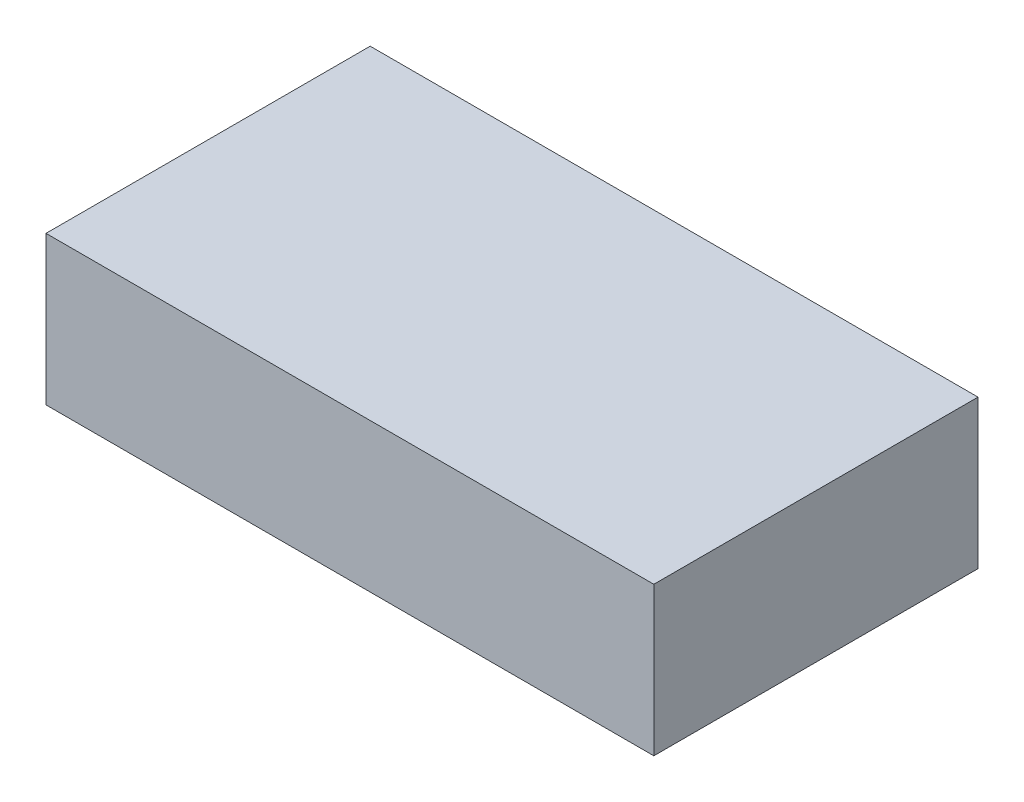
SolidWorks part; units mm, degrees
ref_plane "Front Plane" through (0, 0, 0) normal (0, 0, 1) x (1, 0, 0)
ref_plane "Top Plane" through (0, 0, 0) normal (0, 1, 0) x (1, 0, 0)
ref_plane "Right Plane" through (0, 0, 0) normal (1, 0, 0) x (0, 0, -1)
sketch "Sketch1" plane through (0, 0, 0) normal (0, 1, 0) x (1, 0, 0)
  line L1 (0, 0) -> (-45, 0)
  line L2 (0, 0) -> (0, 24)
  line L3 (0, 24) -> (-45, 24)
  line L4 (-45, 0) -> (-45, 24)
  dimension "D1" = 45
  dimension "D2" = 24
extrude "Boss-Extrude1" add sketch "Sketch1" along normal blind 11
